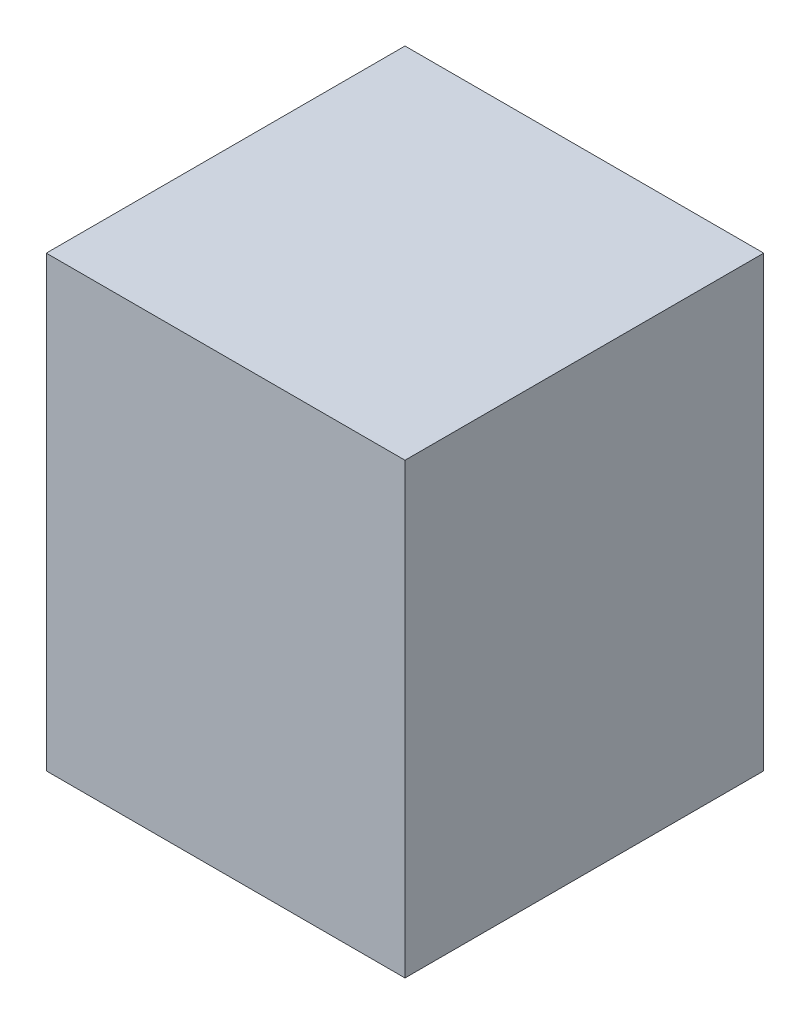
SolidWorks part; units mm, degrees
material "Box"
ref_plane "Front Plane" through (0, 0, 0) normal (0, 0, 1) x (1, 0, 0)
ref_plane "Top Plane" through (0, 0, 0) normal (0, 1, 0) x (1, 0, 0)
ref_plane "Right Plane" through (0, 0, 0) normal (1, 0, 0) x (0, 0, -1)
sketch "Sketch1" plane through (0, 0, 0) normal (0, 1, 0) x (1, 0, 0)
  line L1 (0, 0) -> (80, 0)
  line L2 (0, 0) -> (0, 80)
  line L3 (0, 80) -> (80, 80)
  line L4 (80, 0) -> (80, 80)
  dimension "D1" = 80
  dimension "D2" = 80
extrude "Payload" add sketch "Sketch1" along normal blind 100
